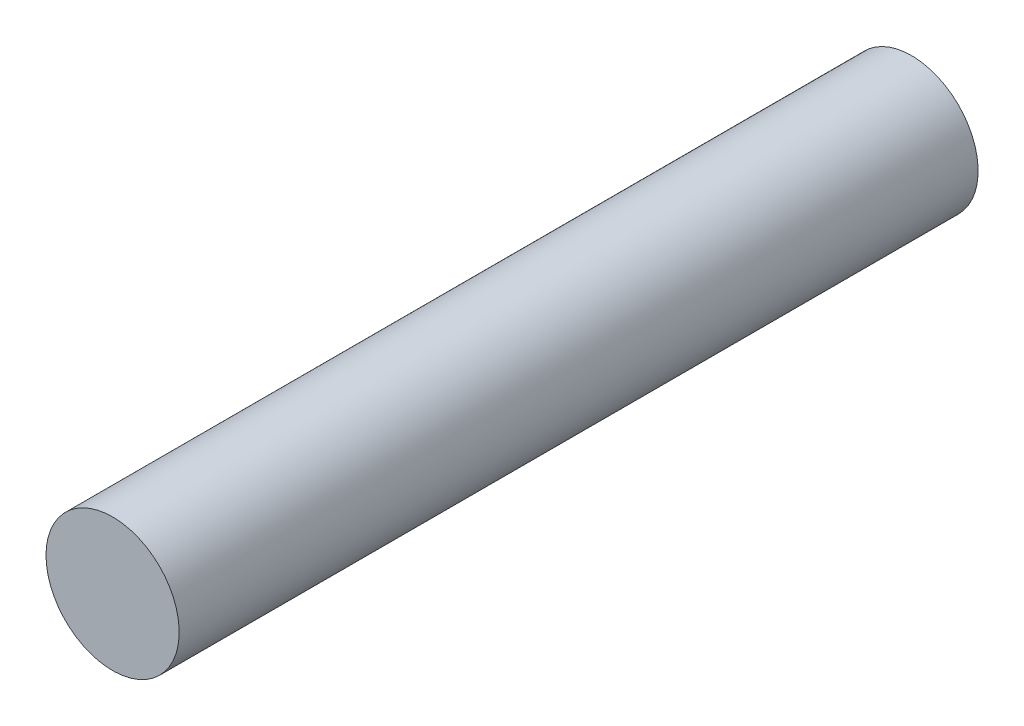
SolidWorks part; units mm, degrees
ref_plane "Front Plane" through (0, 0, 0) normal (0, 0, 1) x (1, 0, 0)
ref_plane "Top Plane" through (0, 0, 0) normal (0, 1, 0) x (1, 0, 0)
ref_plane "Right Plane" through (0, 0, 0) normal (1, 0, 0) x (0, 0, -1)
sketch "Sketch1" plane through (0, 0, 0) normal (0, 0, 1) x (1, 0, 0)
  circle A0 centre (0, 0) radius 1.5875
  dimension "D1" = 3.175
extrude "Boss-Extrude1" add sketch "Sketch1" along normal blind 19.05
